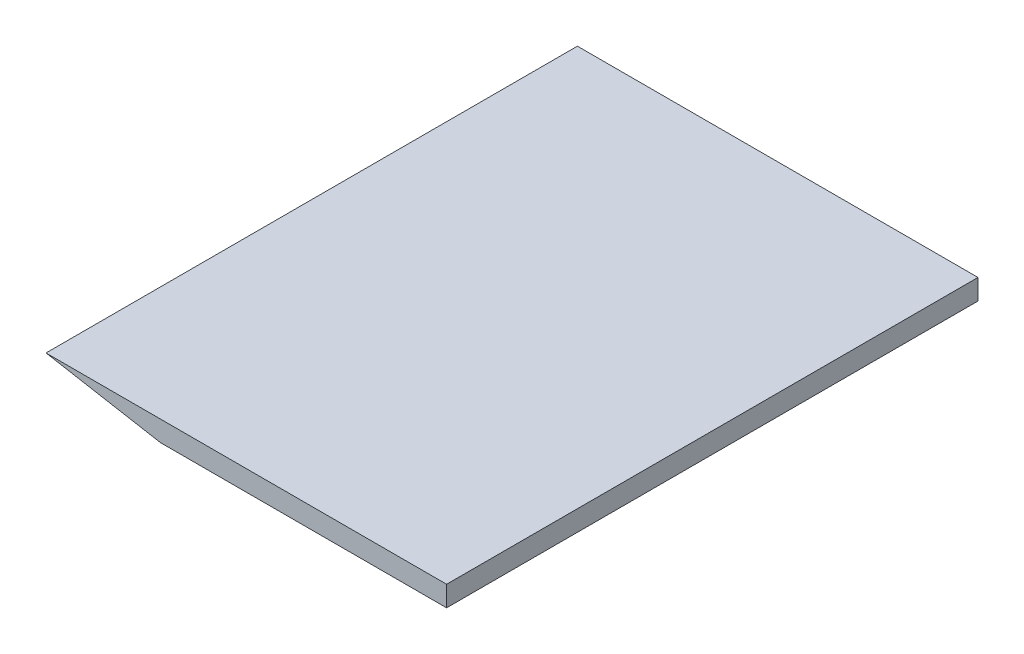
SolidWorks part; units mm, degrees
ref_plane "Front Plane" through (0, 0, 0) normal (0, 0, 1) x (1, 0, 0)
ref_plane "Top Plane" through (0, 0, 0) normal (0, 1, 0) x (1, 0, 0)
ref_plane "Right Plane" through (0, 0, 0) normal (1, 0, 0) x (0, 0, -1)
sketch "Sketch1" plane through (0, 0, 0) normal (0, 0, 1) x (1, 0, 0)
  line L0 (0, 0) -> (98, 0)
  line L1 (98, 0) -> (98, -5)
  line L2 (98, -5) -> (28, -5)
  line L3 (28, -5) -> (0, 0)
  dimension "D1" = 70
  dimension "D2" = 28
  dimension "D3" = 5
extrude "Boss-Extrude1" add sketch "Sketch1" along normal blind 130
